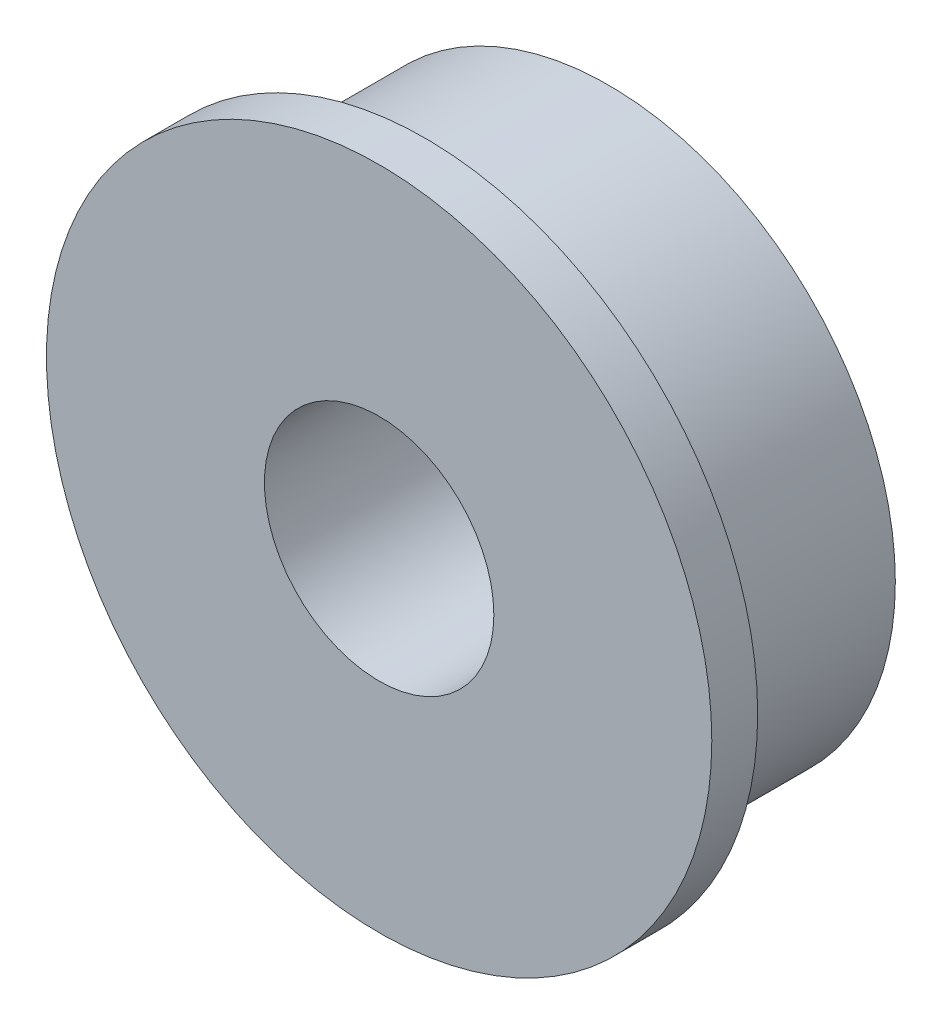
SolidWorks part; units mm, degrees
ref_plane "前视基准面" through (0, 0, 0) normal (0, 0, 1) x (1, 0, 0)
ref_plane "上视基准面" through (0, 0, 0) normal (0, 1, 0) x (1, 0, 0)
ref_plane "右视基准面" through (0, 0, 0) normal (1, 0, 0) x (0, 0, -1)
other "Configuration Table"
sketch "草图1" plane through (0, 0, 0) normal (0, 0, 1) x (1, 0, 0)
  circle A0 centre (0, 0) radius 2
  circle A1 centre (0, 0) radius 5
  dimension "D1" = 4
  dimension "D2" = 10
extrude "凸台-拉伸1" add sketch "草图1" along normal blind 4
sketch "草图2" plane through (0, 0, 4) normal (0, 0, 1) x (1, 0, 0)
  circle A0 centre (0, 0) radius 5.8
  circle A1 centre (0, 0) radius 2 construction
  circle A2 centre (0, 0) radius 2
  dimension "D1" = 11.6
extrude "凸台-拉伸2" add sketch "草图2" against normal blind 0.8
